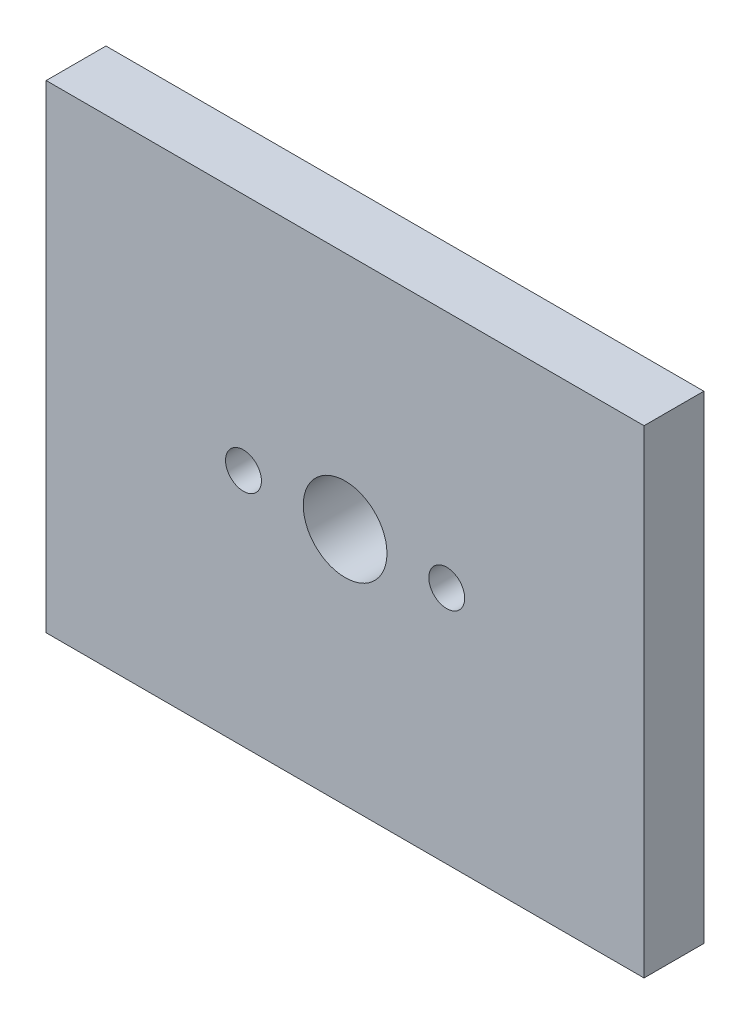
SolidWorks part; units mm, degrees
ref_plane "Plan de face" through (0, 0, 0) normal (0, 0, 1) x (1, 0, 0)
ref_plane "Plan de dessus" through (0, 0, 0) normal (0, 1, 0) x (1, 0, 0)
ref_plane "Plan de droite" through (0, 0, 0) normal (1, 0, 0) x (0, 0, -1)
sketch "Esquisse1" plane through (0, 0, 0) normal (0, 0, 1) x (1, 0, 0)
  line L1 (25, -20) -> (-25, -20)
  line L2 (25, -20) -> (25, 20)
  line L3 (25, 20) -> (-25, 20)
  line L4 (-25, -20) -> (-25, 20)
  line L5 (25, -20) -> (-25, 20) construction
  line L6 (25, 20) -> (-25, -20) construction
  point P0 (0, 0)
  dimension "D1" = 40
  dimension "D2" = 50
extrude "Boss.-Extru.1" add sketch "Esquisse1" along normal blind 5
sketch "Esquisse2" plane through (0, 0, 0) normal (0, 0, -1) x (-1, 0, 0)
  line L0 (-8.5, 0) -> (8.5, 0) construction
  circle A0 centre (0, 0) radius 12
  circle A1 centre (-8.5, 0) radius 1.5
  circle A2 centre (8.5, 0) radius 1.5
  circle A3 centre (0, 0) radius 3.5
  dimension "D1" = 24
  dimension "D2" = 3
  dimension "D3" = 3
  dimension "D5" = 7
  dimension "D4" = 17
extrude "Enlèv. mat.-Extru.1" cut sketch "Esquisse2" against normal blind 10 contours A1 | A3 | A2
